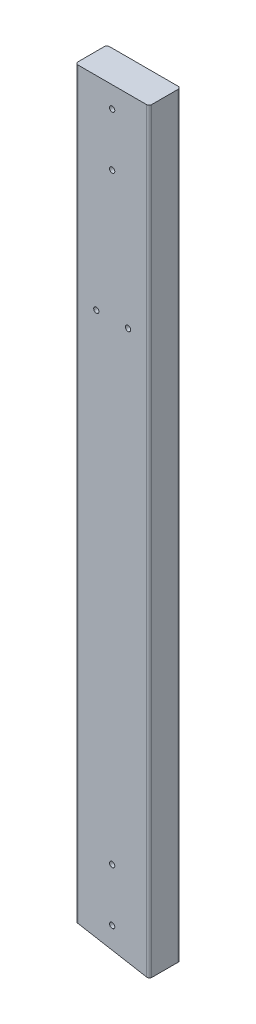
SolidWorks part; units mm, degrees
ref_plane "Front" through (0, 0, 0) normal (0, 0, 1) x (1, 0, 0)
ref_plane "Top" through (0, 0, 0) normal (0, 1, 0) x (1, 0, 0)
ref_plane "Right" through (0, 0, 0) normal (1, 0, 0) x (0, 0, -1)
sketch "Sketch1" plane through (0, 0, 0) normal (0, 1, 0) x (1, 0, 0)
  line L1 (44.45, 19.05) -> (-44.45, 19.05)
  line L2 (44.45, 19.05) -> (44.45, -19.05)
  line L3 (44.45, -19.05) -> (-44.45, -19.05)
  line L4 (-44.45, 19.05) -> (-44.45, -19.05)
  line L5 (44.45, 19.05) -> (-44.45, -19.05) construction
  line L6 (44.45, -19.05) -> (-44.45, 19.05) construction
  point P0 (0, 0)
  dimension "D1" = 88.9
  dimension "D2" = 38.1
extrude "Boss-Extrude1" add sketch "Sketch1" along normal blind 909.6375
sketch "Sketch2" plane through (0, 0, 19.05) normal (0, 0, 1) x (1, 0, 0)
  line L0 (44.45, 0) -> (-44.45, 15.6755)
  line L1 (-44.45, 909.6375) -> (-44.45, 0) construction
  line L2 (-44.45, 15.6755) -> (-44.45, 0)
  line L3 (-44.45, 0) -> (44.45, 0)
  dimension "D1" = 10
extrude "Cut-Extrude1" cut sketch "Sketch2" against normal blind 1257.6368
hole_wizard "1/4 (0.25) Diameter Hole2" positions "Sketch8" profile "Sketch7" hole size "1/4" standard "ANSI Inch" end condition through all
sketch "Sketch8" plane through (0, 0, 19.05) normal (0, 0, 1) x (1, 0, 0)
  line L0 (-44.45, 909.6375) -> (44.45, 909.6375) construction
  line L1 (44.45, 909.6375) -> (44.45, 0) construction
  line L2 (-44.45, 909.6375) -> (-44.45, 15.6755) construction
  point P0 (0, 33.6296)
  point P3 (0, 97.1296)
  point P6 (19.05, 665.228)
  point P9 (-19.05, 665.228)
  point P12 (0, 820.7375)
  point P15 (0, 884.2375)
  point P22 (0, 909.6375)
  dimension "D1" = 25.4
  dimension "D2" = 88.9
  dimension "D3" = 244.4095
  dimension "D4" = 25.4
  dimension "D5" = 25.4
  dimension "D6" = 33.6296
  dimension "D7" = 97.1296
sketch "Sketch7" plane through (0, 33.6296, 19.05) normal (1, 0, 0) x (0, -1, 0)
  line L0 (0, 0) -> (0, 38.1)
  line L1 (0, 38.1) -> (3.175, 38.1)
  line L2 (3.175, 38.1) -> (3.175, 0)
  line L5 (3.175, 0) -> (0, 0)
  line L11 (0, -6.35) -> (0, 107.95) construction
  dimension "Thru Hole Dia." = 6.35
  dimension "Thru Hole Depth" = 38.1
fillet "Fillet1" radius 3.175 4 edges at (-44.45, 462.6565, -19.05) (44.45, 454.8187, -19.05) (-44.45, 462.6565, 19.05) (44.45, 454.8187, 19.05)
